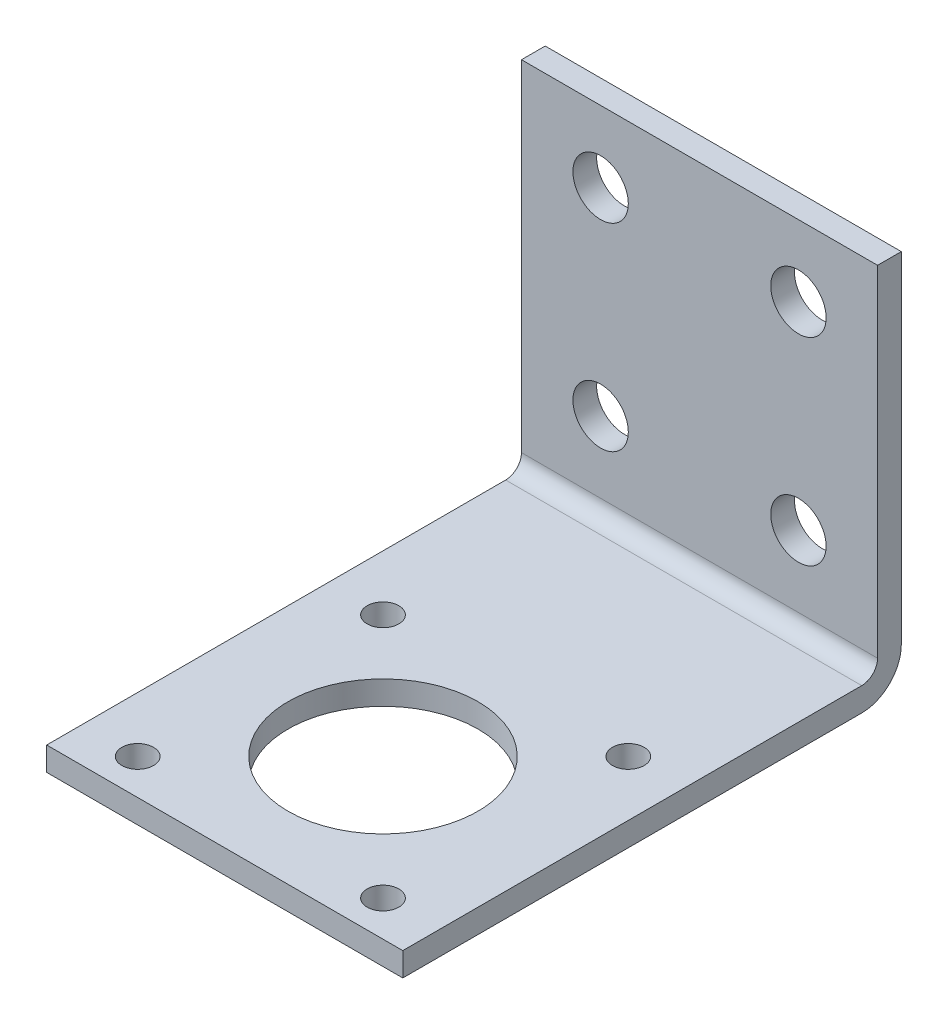
SolidWorks part; units mm, degrees
material "1060 Alloy"
ref_plane "Спереди" through (0, 0, 0) normal (0, 0, 1) x (1, 0, 0)
ref_plane "Сверху" through (0, 0, 0) normal (0, 1, 0) x (1, 0, 0)
ref_plane "Справа" through (0, 0, 0) normal (1, 0, 0) x (0, 0, -1)
sketch "Sketch1" plane through (0, 0, 0) normal (1, 0, 0) x (0, 0, -1)
  line L0 (0, 0) -> (0, 48)
  line L1 (0, 48) -> (-3, 48)
  line L2 (-3, 48) -> (-3, 3)
  line L3 (-3, 3) -> (-63, 3)
  line L4 (-63, 3) -> (-63, 0)
  line L5 (-63, 0) -> (0, 0)
  dimension "D1" = 3
  dimension "D2" = 3
  dimension "D3" = 60
  dimension "D4" = 45
extrude "Boss-Extrude1" add sketch "Sketch1" along normal blind 45
fillet "Fillet1" radius 2 1 edges at (22.5, 3, 3)
fillet "Fillet2" radius 5 1 edges at (22.5, 0, 0)
sketch "Sketch2" plane through (0, 0, 0) normal (0, -1, 0) x (1, 0, 0)
  line L0 (38, 58.5) -> (38, 27.5) construction
  line L1 (38, 27.5) -> (7, 27.5) construction
  line L2 (45, 63) -> (0, 63) construction
  circle A0 centre (38, 58.5) radius 2
  circle A1 centre (38, 27.5) radius 2
  circle A2 centre (7, 58.5) radius 2
  circle A3 centre (7, 27.5) radius 2
  circle A4 centre (22.5, 43) radius 12
  point P10 (38, 43)
  point P11 (22.5, 27.5)
  point P12 (22.5, 63)
  dimension "D1" = 4
  dimension "D2" = 24
  dimension "D3" = 31
  dimension "D4" = 20
extrude "Cut-Extrude1" cut sketch "Sketch2" against normal up to next
sketch "Sketch3" plane through (0, 0, 3) normal (0, 0, 1) x (1, 0, 0)
  line L0 (35, 39) -> (35, 14) construction
  line L1 (35, 14) -> (10, 14) construction
  line L2 (10, 14) -> (10, 39) construction
  line L3 (10, 39) -> (35, 39) construction
  line L4 (45, 48) -> (45, 5) construction
  line L5 (45, 48) -> (0, 48) construction
  circle A0 centre (35, 39) radius 3.5
  circle A1 centre (35, 14) radius 3.5
  circle A2 centre (10, 39) radius 3.5
  circle A3 centre (10, 14) radius 3.5
  point P8 (45, 26.5)
  point P9 (22.5, 48)
  point P12 (22.5, 39)
  point P15 (35, 26.5)
  dimension "D1" = 7
  dimension "D2" = 25
extrude "Cut-Extrude2" cut sketch "Sketch3" against normal through all
